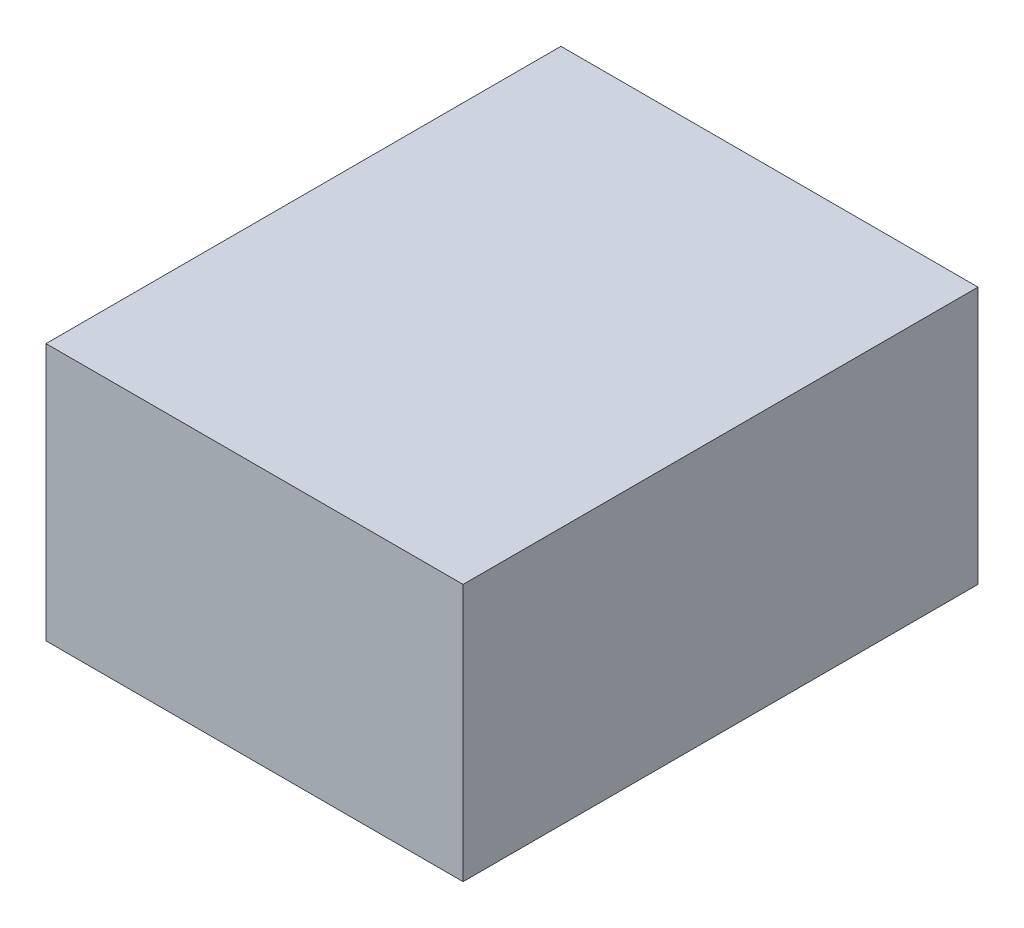
SolidWorks part; units mm, degrees
ref_plane "Front Plane" through (0, 0, 0) normal (0, 0, 1) x (1, 0, 0)
ref_plane "Top Plane" through (0, 0, 0) normal (0, 1, 0) x (1, 0, 0)
ref_plane "Right Plane" through (0, 0, 0) normal (1, 0, 0) x (0, 0, -1)
sketch "Sketch1" plane through (0, 0, 0) normal (0, 1, 0) x (1, 0, 0)
  line L1 (0, 0) -> (16.2, 0)
  line L2 (0, 0) -> (0, 20)
  line L3 (0, 20) -> (16.2, 20)
  line L4 (16.2, 0) -> (16.2, 20)
extrude "Boss-Extrude1" add sketch "Sketch1" along normal blind 10
